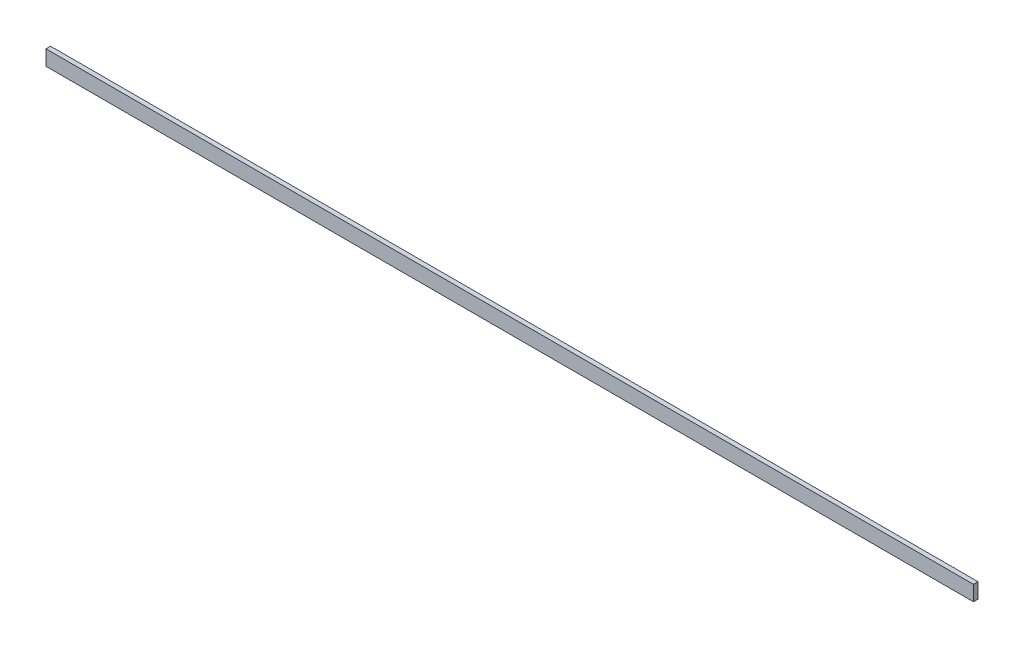
SolidWorks part; units mm, degrees
ref_plane "Front Plane" through (0, 0, 0) normal (0, 0, 1) x (1, 0, 0)
ref_plane "Top Plane" through (0, 0, 0) normal (0, 1, 0) x (1, 0, 0)
ref_plane "Right Plane" through (0, 0, 0) normal (1, 0, 0) x (0, 0, -1)
sketch "Sketch1" plane through (0, 0, 0) normal (0, 0, 1) x (1, 0, 0)
  line L3 (0, 10) -> (0, 0)
  line L5 (0, 0) -> (612, 0)
  line L6 (612, 0) -> (612, 10)
  line L7 (0, 10) -> (612, 10)
  dimension "D2" = 10
extrude "Boss-Extrude1" add sketch "Sketch1" along normal blind 3 contours L3 L5 L6 L7
